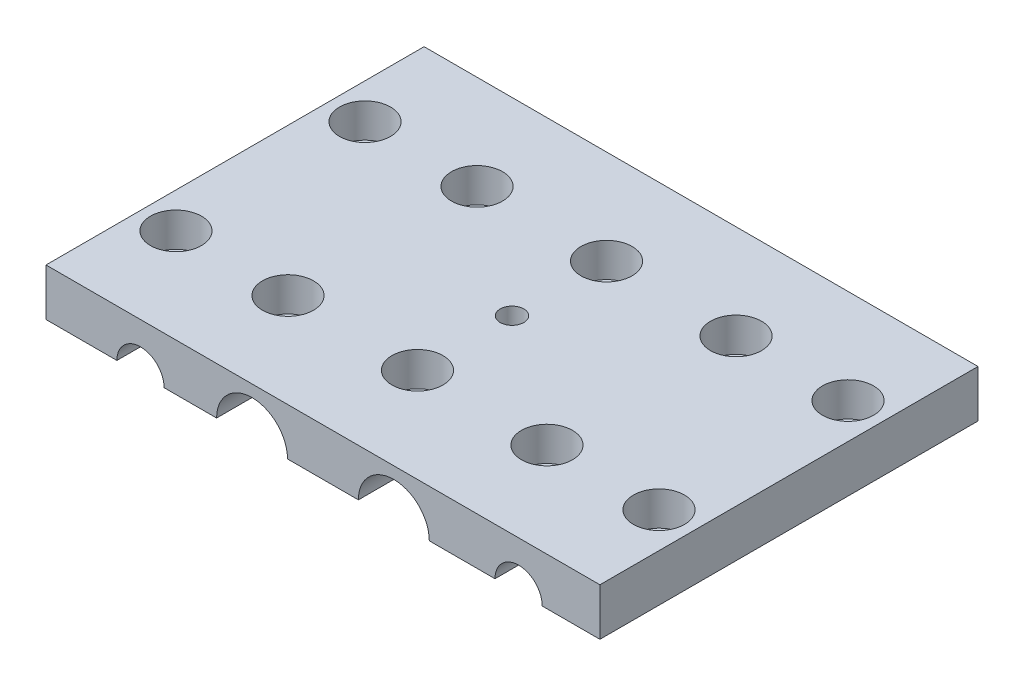
SolidWorks part; units mm, degrees
material "Copper"
ref_plane "Front Plane" through (0, 0, 0) normal (0, 0, 1) x (1, 0, 0)
ref_plane "Top Plane" through (0, 0, 0) normal (0, 1, 0) x (1, 0, 0)
ref_plane "Right Plane" through (0, 0, 0) normal (1, 0, 0) x (0, 0, -1)
sketch "Sketch1" plane through (0, 0, 0) normal (0, 1, 0) x (1, 0, 0)
  line L1 (-37.211, 25.4) -> (37.211, 25.4)
  line L2 (-37.211, 25.4) -> (-37.211, -25.4)
  line L3 (-37.211, -25.4) -> (37.211, -25.4)
  line L4 (37.211, 25.4) -> (37.211, -25.4)
  dimension "D1" = 50.8
  dimension "D2" = 74.422
  dimension "D3" = 37.211
  dimension "D4" = 25.4
extrude "Boss-Extrude1" add sketch "Sketch1" along normal blind 6.35
sketch "Sketch2" plane through (0, 0, 25.4) normal (0, 0, 1) x (1, 0, 0)
  line L0 (-37.211, 0) -> (37.211, 0) construction
  line L1 (-37.211, 6.35) -> (-37.211, 0) construction
  circle A0 centre (-24.511, 0) radius 3.175
  circle A1 centre (26.289, 0) radius 3.175
  dimension "D3" = 6.35
  dimension "D1" = 50.8
  dimension "D2" = 12.7
extrude "Cut-Extrude1" cut sketch "Sketch2" against normal through all
sketch "Sketch3" plane through (0, 0, 25.4) normal (0, 0, 1) x (1, 0, 0)
  line L0 (-21.336, 0) -> (23.114, 0) construction
  circle A0 centre (-9.525, 0) radius 4.7625
  circle A1 centre (9.525, 0) radius 4.7625
  dimension "D1" = 9.525
  dimension "D2" = 19.05
  dimension "D3" = 9.525
extrude "Cut-Extrude2" cut sketch "Sketch3" against normal through all
hole_wizard "#8 Clearance Hole1" positions "Sketch5" profile "Sketch4" hole size "#8" standard "ANSI Inch" end condition through all
sketch "Sketch5" plane through (0, 6.35, 0) normal (0, 1, 0) x (1, 0, 0)
  line L2 (37.211, 25.4) -> (-37.211, 25.4) construction
  line L3 (-37.211, -25.4) -> (37.211, -25.4) construction
  line L4 (-37.211, 25.4) -> (-37.211, -25.4) construction
  line L5 (37.211, -25.4) -> (37.211, 25.4) construction
  point P0 (-32.4485, 12.7)
  point P2 (-32.4485, -12.7)
  point P4 (-17.399, -12.7)
  point P6 (0, -12.7)
  point P8 (17.399, -12.7)
  point P10 (32.4485, -12.7)
  point P12 (32.4485, 12.7)
  point P14 (17.399, 12.7)
  point P16 (0, 12.7)
  point P18 (-17.399, 12.7)
  dimension "D1" = 12.7
  dimension "D2" = 12.7
  dimension "D3" = 4.7625
  dimension "D4" = 4.7625
  dimension "D5" = 19.812
  dimension "D6" = 19.812
sketch "Sketch4" plane through (-32.4485, 6.35, -12.7) normal (1, 0, 0) x (0, 0, 1)
  line L0 (0, 0) -> (0, 6.35)
  line L1 (0, 6.35) -> (2.2479, 6.35)
  line L2 (2.2479, 6.35) -> (2.2479, 0)
  line L5 (2.2479, 0) -> (0, 0)
  line L11 (0, -6.35) -> (0, 107.95) construction
  dimension "Thru Hole Dia." = 4.4958
  dimension "Thru Hole Depth" = 6.35
sketch "Sketch6" plane through (0, 6.35, 0) normal (0, 1, 0) x (1, 0, 0)
  circle A0 centre (-32.4485, 12.7) radius 3.429
  circle A1 centre (-17.399, 12.7) radius 3.429
  circle A2 centre (0, 12.7) radius 3.429
  circle A3 centre (17.399, 12.7) radius 3.429
  circle A4 centre (32.4485, 12.7) radius 3.429
  circle A5 centre (32.4485, -12.7) radius 3.429
  circle A6 centre (17.399, -12.7) radius 3.429
  circle A7 centre (0, -12.7) radius 3.429
  circle A8 centre (-17.399, -12.7) radius 3.429
  circle A9 centre (-32.4485, -12.7) radius 3.429
  dimension "D1" = 6.858
extrude "Cut-Extrude3" cut sketch "Sketch6" against normal blind 4.572
sketch "Sketch7" plane through (0, 6.35, 0) normal (0, 1, 0) x (1, 0, 0)
  circle A0 centre (0, 0) radius 1.5875
  dimension "D1" = 3.175
extrude "Cut-Extrude4" cut sketch "Sketch7" against normal through all
